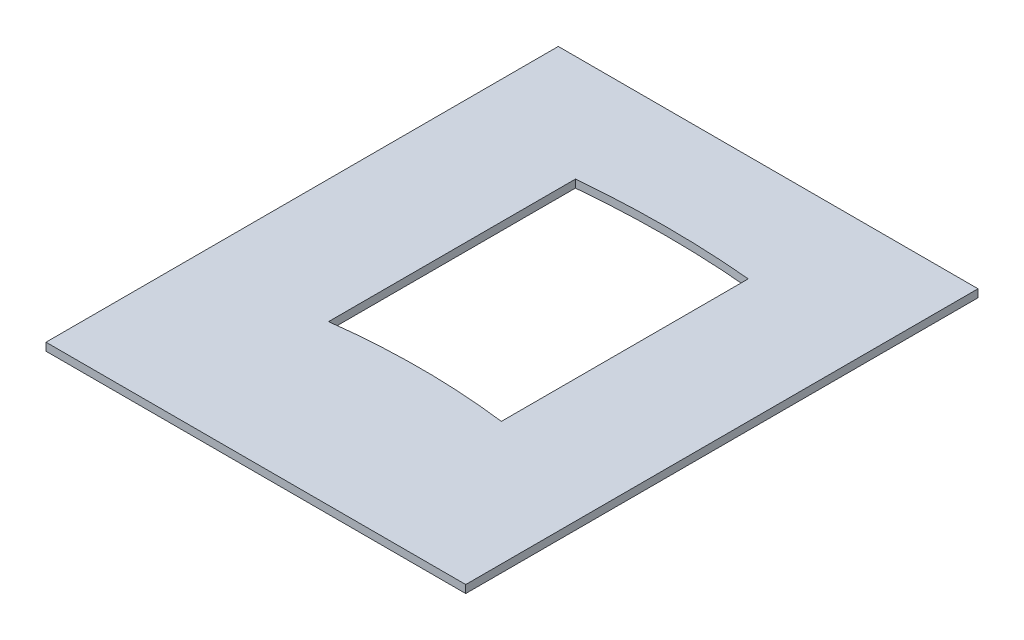
SolidWorks part; units mm, degrees
material "Copper"
ref_plane "Front" through (0, 0, 0) normal (0, 0, 1) x (1, 0, 0)
ref_plane "Top" through (0, 0, 0) normal (0, 1, 0) x (1, 0, 0)
ref_plane "Right" through (0, 0, 0) normal (1, 0, 0) x (0, 0, -1)
sketch "Sketch1" plane through (0, 0, 0) normal (0, 1, 0) x (1, 0, 0)
  line L0 (0, 0) -> (0, 4) construction
  line L2 (-1.4, 4) -> (-1.4, 0)
  line L3 (1.4, 4) -> (1.4, 0)
  line L4 (-3.4, 5.722) -> (-3.4, -2.5775)
  line L5 (3.4, 5.722) -> (3.4, -2.5775)
  line L6 (-3.4, 5.722) -> (3.4, 5.722)
  line L7 (-3.4, -2.5775) -> (3.4, -2.5775)
  arc A1 (-1.4, 0) -> (1.4, 0) centre (0, -10.9105) cw
  arc A2 (-1.4, 4) -> (1.4, 4) centre (0, -10.9345) cw
  arc A5 (-3.4, -2.5775) -> (3.4, -2.5775) centre (0, -10.9105) cw construction
  arc A7 (-3.4, 5.722) -> (3.4, 5.722) centre (0, -10.9345) cw construction
  point P6 (0, 4)
  dimension "D1" = 4
  dimension "D2" = 11
  dimension "D4" = 15
  dimension "D3" = 2.8
  dimension "D5" = 2
extrude "Boss-Extrude1" add sketch "Sketch1" along normal blind 0.127
